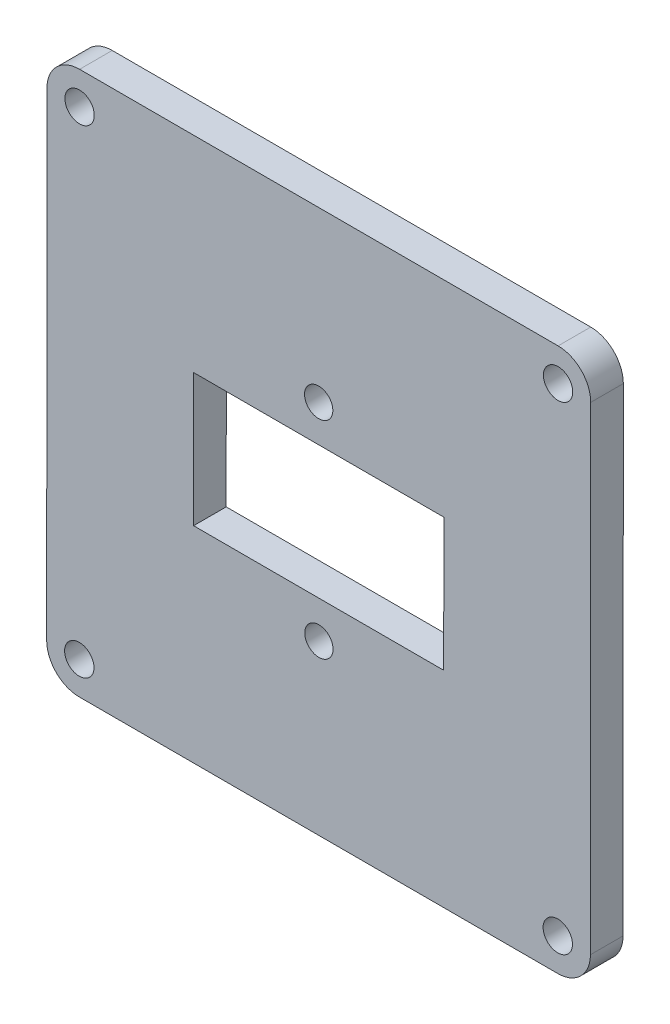
SolidWorks part; units mm, degrees
ref_plane "前视基准面" through (0, 0, 0) normal (0, 0, 1) x (1, 0, 0)
ref_plane "上视基准面" through (0, 0, 0) normal (0, 1, 0) x (1, 0, 0)
ref_plane "右视基准面" through (0, 0, 0) normal (1, 0, 0) x (0, 0, -1)
ref_plane "基准面4" through (0, 0, 3) normal (0, 0, 1) x (1, 0, 0)
sketch "草图1" plane through (0, 0, 3) normal (0, 0, 1) x (1, 0, 0)
  line L0 (291.111, 60.8503) -> (291.0848, 16.8507)
  line L1 (294.083, 13.8489) -> (338.0829, 13.8227)
  line L2 (341.0847, 16.8209) -> (341.1109, 60.8205)
  line L3 (338.1127, 63.8223) -> (294.1128, 63.8486)
  line L4 (304.6017, 44.9425) -> (327.6024, 44.9288)
  line L5 (327.6024, 44.9288) -> (327.5951, 32.7283)
  line L6 (327.5951, 32.7283) -> (304.5944, 32.7421)
  line L7 (304.5944, 32.7421) -> (304.6017, 44.9425)
  arc A0 (291.0848, 16.8507) -> (294.083, 13.8489) centre (294.0848, 16.8489) ccw
  arc A1 (338.0829, 13.8227) -> (341.0847, 16.8209) centre (338.0847, 16.8227) ccw
  arc A2 (341.1109, 60.8205) -> (338.1127, 63.8223) centre (338.111, 60.8223) ccw
  arc A3 (294.1128, 63.8486) -> (291.111, 60.8503) centre (294.111, 60.8486) ccw
  circle A4 centre (338.0847, 16.8227) radius 1.35
  circle A5 centre (294.111, 60.8486) radius 1.35
  circle A6 centre (338.111, 60.8223) radius 1.35
  circle A7 centre (294.0848, 16.8489) radius 1.35
  circle A8 centre (316.1188, 29.3164) radius 1.3
  circle A9 centre (316.098, 48.3168) radius 1.3
extrude "凸台-拉伸1" add sketch "草图1" against normal blind 3
